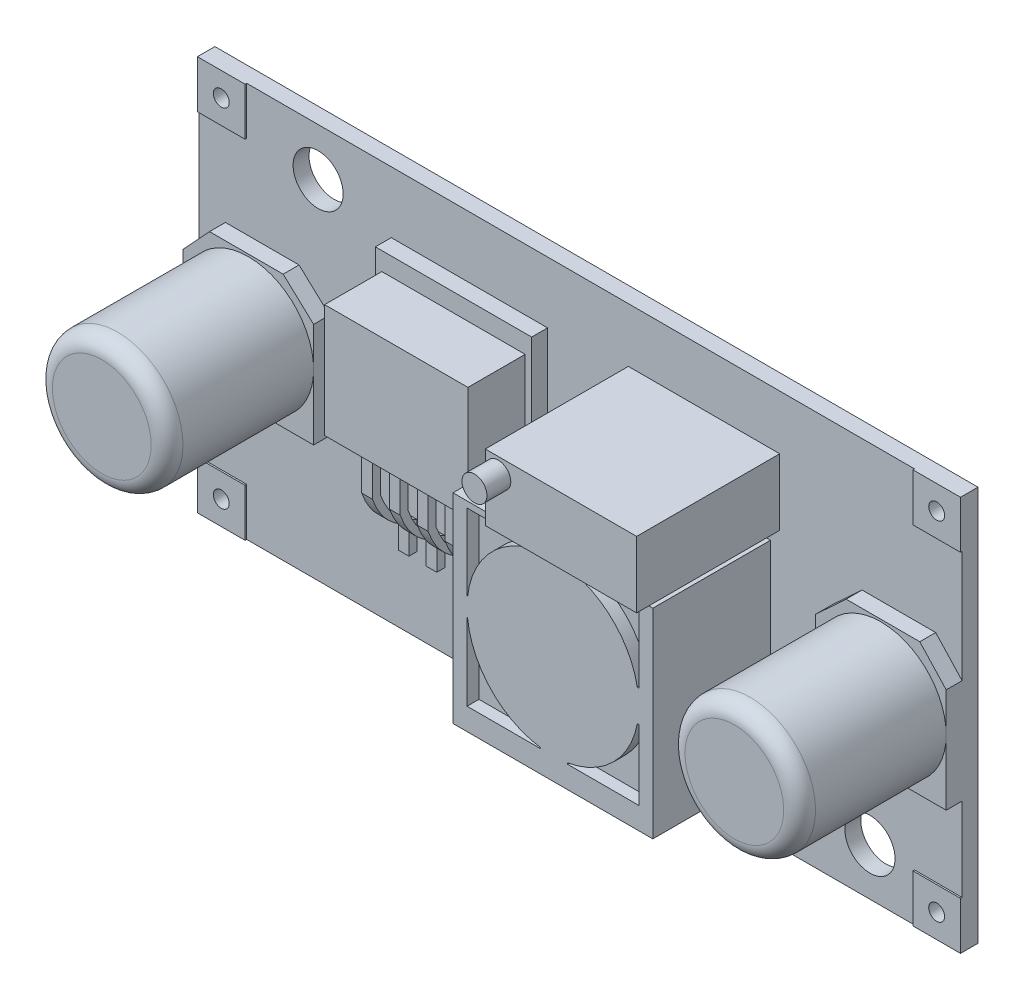
SolidWorks part; units mm, degrees
ref_plane "Front Plane" through (0, 0, 0) normal (0, 0, 1) x (1, 0, 0)
ref_plane "Top Plane" through (0, 0, 0) normal (0, 1, 0) x (1, 0, 0)
ref_plane "Right Plane" through (0, 0, 0) normal (1, 0, 0) x (0, 0, -1)
sketch "Sketch1" plane through (0, 0, 0) normal (0, 0, 1) x (1, 0, 0)
  line L0 (18.2052, -9.425) -> (-16.5068, 9.425) construction
  line L1 (24, -12.425) -> (-24, -12.425)
  line L2 (24, -12.425) -> (24, 12.425)
  line L3 (24, 12.425) -> (-24, 12.425)
  line L4 (-24, -12.425) -> (-24, 12.425)
  line L5 (24, -12.425) -> (-24, 12.425) construction
  line L6 (24, 12.425) -> (-24, -12.425) construction
  circle A0 centre (-16.5068, 9.425) radius 1.575
  circle A1 centre (18.2052, -9.425) radius 1.575
  point P0 (0, 0)
  dimension "D1" = 48
  dimension "D6" = 3.15
  dimension "D7" = 3.15
  dimension "D2" = 24.85
  dimension "D3" = 3
  dimension "D4" = 3
  dimension "D5" = 39.5
extrude "Boss-Extrude1" add sketch "Sketch1" along normal blind 1
sketch "Sketch2" plane through (0, 0, 1) normal (0, 0, 1) x (1, 0, 0)
  line L0 (24, -12.425) -> (24, 12.425) construction
  line L1 (-24, 12.425) -> (-21, 12.425)
  line L2 (-24, 12.425) -> (-24, 9.425)
  line L3 (-24, 9.425) -> (-21, 9.425)
  line L4 (-21, 12.425) -> (-21, 9.425)
  line L5 (24, 12.425) -> (-24, 12.425) construction
  line L6 (-24, -12.425) -> (24, -12.425) construction
  line L7 (-24, 12.425) -> (-24, -12.425) construction
  line L8 (-21, -12.425) -> (-21, -9.425)
  line L9 (-24, -9.425) -> (-21, -9.425)
  line L10 (-24, -12.425) -> (-24, -9.425)
  line L11 (-24, -12.425) -> (-21, -12.425)
  line L12 (24, -12.425) -> (21, -12.425)
  line L13 (24, -12.425) -> (24, -9.425)
  line L14 (24, -9.425) -> (21, -9.425)
  line L15 (21, -12.425) -> (21, -9.425)
  line L16 (21, 12.425) -> (21, 9.425)
  line L17 (24, 9.425) -> (21, 9.425)
  line L18 (24, 12.425) -> (24, 9.425)
  line L19 (24, 12.425) -> (21, 12.425)
  dimension "D1" = 3
  dimension "D2" = 3
  dimension "D3" = 3
  dimension "D4" = 3
  dimension "D5" = 3
  dimension "D6" = 3
  dimension "D7" = 3
  dimension "D8" = 3
extrude "Boss-Extrude2" add sketch "Sketch2" along normal blind 0.1
sketch "Sketch3" plane through (0, 0, 1.1) normal (0, 0, 1) x (1, 0, 0)
  line L0 (22.5, -10.925) -> (-22.5, -10.925) construction
  line L1 (-22.5, -10.925) -> (-22.5, 10.925) construction
  line L2 (-22.5, 10.925) -> (22.5, 10.925) construction
  line L3 (22.5, 10.925) -> (22.5, -10.925) construction
  line L6 (21, 12.425) -> (21, 9.425) construction
  line L7 (21, 9.425) -> (24, 9.425) construction
  line L8 (-21, -12.425) -> (-21, -9.425) construction
  line L9 (-21, -9.425) -> (-24, -9.425) construction
  circle A0 centre (-22.5, 10.925) radius 0.5
  circle A1 centre (-22.5, -10.925) radius 0.5
  circle A2 centre (22.5, -10.925) radius 0.5
  circle A3 centre (22.5, 10.925) radius 0.5
  point P11 (21, 10.925)
  point P14 (22.5, 9.425)
  point P19 (-21, -10.925)
  point P22 (-22.5, -9.425)
  dimension "D1" = 1
  dimension "D2" = 1
  dimension "D3" = 1
  dimension "D4" = 1
extrude "Cut-Extrude1" cut sketch "Sketch3" against normal blind 5
sketch "Sketch4" plane through (0, 0, 1) normal (0, 0, 1) x (1, 0, 0)
  line L1 (24, -9.425) -> (24, 9.425) construction
  line L2 (-24, 9.425) -> (-24, -9.425) construction
  line L3 (21, 12.425) -> (-21, 12.425) construction
  line L5 (-24, 2.3832) -> (-22.3385, 4.175)
  line L6 (-22.3385, 4.175) -> (-17.7064, 4.175)
  line L7 (-24, -4.175) -> (-15.79, -4.175)
  line L8 (-24, -4.175) -> (-24, 2.3832)
  line L9 (-22.3385, 4.175) -> (-17.7064, 4.175)
  line L10 (-15.79, -4.175) -> (-15.79, 2.398)
  line L11 (-24, -4.175) -> (-16.7039, 3.2455) construction
  line L12 (-23.1449, 3.3054) -> (-15.79, -4.175) construction
  line L13 (-17.7064, 4.175) -> (-15.79, 2.398)
  line L14 (23.1449, 3.3054) -> (15.79, -4.175) construction
  line L15 (24, -4.175) -> (16.7039, 3.2455) construction
  line L16 (17.7064, 4.175) -> (15.79, 2.398)
  line L17 (15.79, -4.175) -> (15.79, 2.398)
  line L18 (22.3385, 4.175) -> (17.7064, 4.175)
  line L19 (24, -4.175) -> (24, 2.3832)
  line L20 (24, -4.175) -> (15.79, -4.175)
  line L21 (22.3385, 4.175) -> (17.7064, 4.175)
  line L22 (24, 2.3832) -> (22.3385, 4.175)
  point P13 (-19.895, 0)
  point P28 (19.895, 0)
  dimension "D1" = 8.21
  dimension "D2" = 6.573
  dimension "D3" = 10.4905
  dimension "D4" = 4.6322
  dimension "D5" = 2.4435
  dimension "D6" = 6.5582
  dimension "D7" = 2.6135
  dimension "D8" = 6.573
  dimension "D9" = 8.21
  dimension "D10" = 10.4905
  dimension "D11" = 6.5582
  dimension "D12" = 2.4435
  dimension "D13" = 4.6322
  dimension "D14" = 10.4065
  dimension "D15" = 12.425
  dimension "D16" = 12.425
  dimension "D17" = 10.4065
  dimension "D18" = 1.3671
  dimension "D19" = 1.186
extrude "Boss-Extrude3" add sketch "Sketch4" along normal blind 1 contours L13 L6 L5 L8 L7 L10 | L19 L22 L18 L16 L17 L20
sketch "Sketch5" plane through (0, 0, 2) normal (0, 0, 1) x (1, 0, 0)
  line L6 (24, -4.175) -> (15.79, -4.175) construction
  line L7 (24, -4.175) -> (24, 2.3832) construction
  line L8 (-24, 2.3832) -> (-24, -4.175) construction
  line L10 (-24, -4.175) -> (-15.79, -4.175) construction
  circle A0 centre (-19.895, -0.07) radius 4.105
  circle A1 centre (19.895, -0.07) radius 4.105
  dimension "D1" = 8.21
  dimension "D2" = 8.21
extrude "Boss-Extrude4" add sketch "Sketch5" along normal blind 9.22
fillet "Fillet1" radius 1 1 edges at (-15.79, -0.07, 11.22)
fillet "Fillet2" radius 1 1 edges at (15.79, -0.07, 11.22)
sketch "Sketch6" plane through (0, 0, 1) normal (0, 0, 1) x (1, 0, 0)
  line L5 (-11.9064, 8.5637) -> (-2.0764, 8.5637)
  line L6 (-11.9064, 8.5637) -> (-11.9064, -0.1863)
  line L7 (-11.9064, -0.1863) -> (-2.0764, -0.1863)
  line L8 (-2.0764, 8.5637) -> (-2.0764, -0.1863)
extrude "Boss-Extrude5" add sketch "Sketch6" along normal blind 4.6
sketch "Sketch7" plane through (0, 0, 5.6) normal (0, 0, 1) x (1, 0, 0)
  line L3 (-11.4988, 7.4182) -> (-2.4839, 7.4182)
  line L4 (-11.4988, 0.2879) -> (-2.4839, 0.2879)
  line L5 (-11.4988, 0.2879) -> (-11.4988, 7.4182)
  line L7 (-2.4839, 0.2879) -> (-2.4839, 7.4182)
  line L11 (-11.9064, -0.1863) -> (-2.0764, -0.1863)
  line L12 (-11.9064, -0.1863) -> (-11.9064, 8.5637)
  line L13 (-11.9064, 8.5637) -> (-2.0764, 8.5637)
  line L14 (-2.0764, -0.1863) -> (-2.0764, 8.5637)
  point P6 (-6.9914, 4.1887)
  point P13 (-6.9914, 4.1887)
extrude "Cut-Extrude2" cut sketch "Sketch7" against normal blind 3.6
sketch "Sketch8" plane through (0, 0.2879, 0) normal (0, -1, 0) x (-1, 0, 0)
  line L0 (9.1927, -4.7708) -> (9.1927, -1.0208)
  line L1 (10.9427, -4.7708) -> (10.2713, -4.7708)
  line L2 (10.9427, -4.7708) -> (10.9427, -1.0208)
  line L3 (10.9427, -1.0208) -> (10.2713, -1.0208)
  line L4 (10.2713, -4.7708) -> (10.2713, -1.0208)
  line L5 (9.1927, -4.7708) -> (8.5213, -4.7708)
  line L6 (8.5213, -4.7708) -> (8.5213, -1.0208)
  line L7 (9.1927, -1.0208) -> (8.5213, -1.0208)
  line L8 (7.4427, -4.7708) -> (7.4427, -1.0208)
  line L9 (7.4427, -4.7708) -> (6.7713, -4.7708)
  line L10 (6.7713, -4.7708) -> (6.7713, -1.0208)
  line L11 (7.4427, -1.0208) -> (6.7713, -1.0208)
  line L12 (5.6927, -4.7708) -> (5.6927, -1.0208)
  line L13 (5.6927, -4.7708) -> (5.0213, -4.7708)
  line L14 (5.0213, -4.7708) -> (5.0213, -1.0208)
  line L15 (5.6927, -1.0208) -> (5.0213, -1.0208)
  line L16 (3.9427, -4.7708) -> (3.9427, -1.0208)
  line L17 (3.9427, -4.7708) -> (3.2713, -4.7708)
  line L18 (3.2713, -4.7708) -> (3.2713, -1.0208)
  line L19 (3.9427, -1.0208) -> (3.2713, -1.0208)
  dimension "D1" = 5
extrude "Boss-Extrude6" add sketch "Sketch8" along normal blind 8
sketch "Sketch9" plane through (-3.2713, 0, 0) normal (1, 0, 0) x (0, 0, -1)
  line L0 (-4.7708, 0.2879) -> (-2, 0.2879) construction
  line L2 (-3.8208, 0.2879) -> (-3.8208, -3.4592)
  line L3 (-3.3208, 0.2879) -> (-2, 0.2879)
  line L4 (-3.3208, 0.2879) -> (-3.3208, -3.4592)
  line L5 (-4.7708, -7.7121) -> (-2, -7.7121)
  line L6 (-4.7708, -7.7121) -> (-4.7708, 0.2879)
  line L7 (-1.5208, -5.9544) -> (-1.5208, -7.7121)
  line L10 (-4.7708, 0.2879) -> (-3.8208, 0.2879)
  line L12 (-2, -7.7121) -> (-1.5208, -7.7121)
  line L14 (-2, -0.1863) -> (-1.0208, -0.1863)
  line L15 (-1.0208, -5.9544) -> (-1.0208, -0.1863)
  spline S0 degree 2 poles (-3.8208, -3.4592) (-3.2012, -5.2461) (-1.5208, -5.9544) knots 0 0 0 1 1 1
  spline S1 degree 2 poles (-3.3208, -3.4592) (-2.7012, -5.2461) (-1.0208, -5.9544) knots 0 0 0 1 1 1
  line M1 (-1.0208, -7.7121) -> (-1.0208, -0.1863)
  line M2 (-1.0208, -0.1863) -> (-2, -0.1863)
  line M3 (-2, -0.1863) -> (-2, 0.2879)
  line M4 (-2, 0.2879) -> (-4.7708, 0.2879)
  line M5 (-4.7708, 0.2879) -> (-4.7708, -7.7121)
  line M6 (-4.7708, -7.7121) -> (-1.0208, -7.7121)
extrude "Cut-Extrude3" cut sketch "Sketch9" against normal blind 9 contours S0 L2 L7 M4 M5 M6 | L4 S1 M1 M2 M3 M4
sketch "Sketch10" plane through (0, 0, 1) normal (0, 0, 1) x (1, 0, 0)
  line L5 (11.9464, -8.5637) -> (-0.6236, -8.5637)
  line L6 (11.9464, -8.5637) -> (11.9464, 4.0063)
  line L7 (11.9464, 4.0063) -> (-0.6236, 4.0063)
  line L8 (-0.6236, -8.5637) -> (-0.6236, 4.0063)
extrude "Boss-Extrude7" add sketch "Sketch10" along normal blind 7.4
sketch "Sketch11" plane through (0, 0, 8.4) normal (0, 0, 1) x (1, 0, 0)
  line L0 (0.2614, -1.1682) -> (0.2922, -1.2029)
  line L3 (0.2614, -2.3394) -> (0.2922, -2.3545)
  line L4 (0.2614, -7.1787) -> (4.8799, -7.1787)
  line L5 (0.2614, -7.1787) -> (0.2614, -2.3394)
  line L6 (0.2614, 3.6213) -> (4.9528, 3.6213)
  line L7 (11.0614, -7.1787) -> (11.0614, -2.7691)
  line L8 (0.2614, -7.1787) -> (11.0614, 3.6213) construction
  line L9 (0.2614, 3.6213) -> (11.0614, -7.1787) construction
  line L10 (4.9528, 3.6213) -> (4.9528, 3.5746)
  line L11 (6.2806, 3.6213) -> (6.2806, 3.5857)
  line L12 (10.9698, -0.7882) -> (11.0614, -0.7882)
  line L13 (10.9698, -2.7691) -> (11.0614, -2.7691)
  line L14 (4.8799, -7.1787) -> (4.8799, -7.1218)
  line L15 (6.582, -7.1787) -> (6.582, -7.0996)
  line L16 (6.582, -7.1787) -> (11.0614, -7.1787)
  line L17 (0.2614, -1.1682) -> (0.2614, 3.6213)
  line L18 (6.2806, 3.6213) -> (11.0614, 3.6213)
  line L19 (11.0614, -0.7882) -> (11.0614, 3.6213)
  arc A0 (6.582, -7.0996) -> (10.9698, -2.7691) centre (5.6614, -1.7787) ccw
  arc A1 (0.2922, -2.3545) -> (4.8799, -7.1218) centre (5.6614, -1.7787) ccw
  arc A2 (4.9528, 3.5746) -> (0.2922, -1.2029) centre (5.6614, -1.7787) ccw
  arc A3 (10.9698, -0.7882) -> (6.2806, 3.5857) centre (5.6614, -1.7787) ccw
  point P6 (5.6614, -1.7787)
extrude "Cut-Extrude7" cut sketch "Sketch11" against normal blind 0.75
sketch "Sketch13" plane through (0, 0, 1) normal (0, 0, 1) x (1, 0, 0)
  line L1 (12.527, 4.8371) -> (3.007, 4.8371)
  line L2 (12.527, 4.8371) -> (12.527, 9.0071)
  line L3 (12.527, 9.0071) -> (3.007, 9.0071)
  line L4 (3.007, 4.8371) -> (3.007, 9.0071)
extrude "Boss-Extrude8" add sketch "Sketch13" along normal blind 9
sketch "Sketch14" plane through (0, 0, 10) normal (0, 0, 1) x (1, 0, 0)
  circle A0 centre (3.8265, 8.0224) radius 0.7858
extrude "Boss-Extrude9" add sketch "Sketch14" along normal blind 1.5
